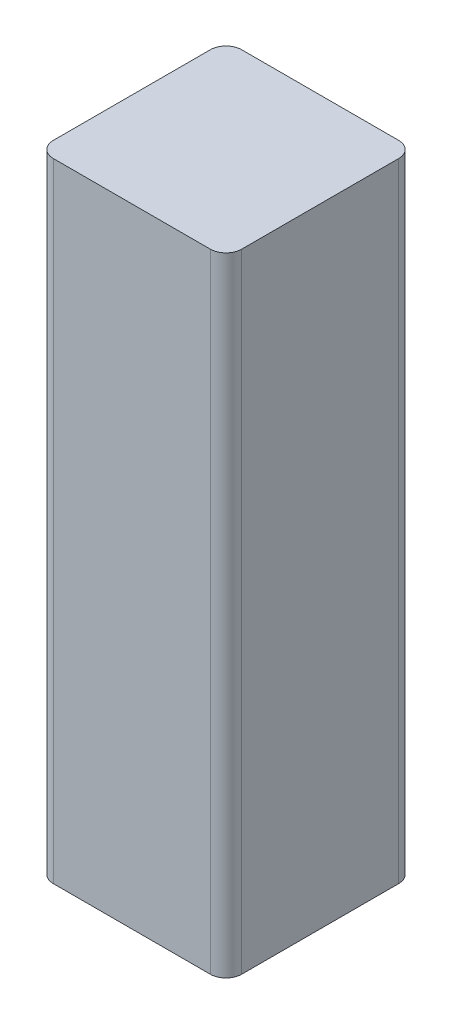
SolidWorks part; units mm, degrees
ref_plane "Front Plane" through (0, 0, 0) normal (0, 0, 1) x (1, 0, 0)
ref_plane "Top Plane" through (0, 0, 0) normal (0, 1, 0) x (1, 0, 0)
ref_plane "Right Plane" through (0, 0, 0) normal (1, 0, 0) x (0, 0, -1)
sketch "Sketch1" plane through (0, 0, 0) normal (0, 1, 0) x (1, 0, 0)
  line L1 (-2.5, -3) -> (2.5, -3)
  line L2 (-3, -2.5) -> (-3, 2.5)
  line L3 (-2.5, 3) -> (2.5, 3)
  line L4 (3, -2.5) -> (3, 2.5)
  line L5 (-3, -3) -> (3, 3) construction
  line L6 (-3, 3) -> (3, -3) construction
  arc A0 (2.5, -3) -> (3, -2.5) centre (2.5, -2.5) ccw
  arc A1 (3, 2.5) -> (2.5, 3) centre (2.5, 2.5) ccw
  arc A2 (-2.5, 3) -> (-3, 2.5) centre (-2.5, 2.5) ccw
  arc A3 (-2.5, -3) -> (-3, -2.5) centre (-2.5, -2.5) cw
  point P0 (0, 0)
  dimension "D1" = 0.5
  dimension "D2" = 6
  dimension "D3" = 6
extrude "Corpo" add sketch "Sketch1" along normal blind 20
